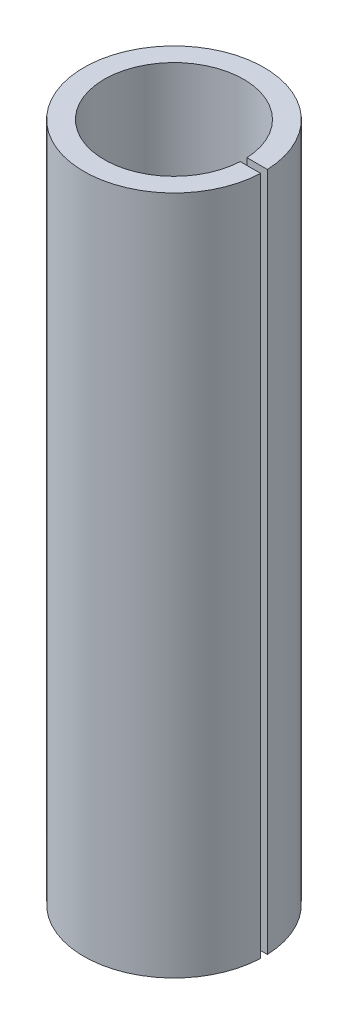
SolidWorks part; units mm, degrees
ref_plane "Front Plane" through (0, 0, 0) normal (0, 0, 1) x (1, 0, 0)
ref_plane "Top Plane" through (0, 0, 0) normal (0, 1, 0) x (1, 0, 0)
ref_plane "Right Plane" through (0, 0, 0) normal (1, 0, 0) x (0, 0, -1)
ref_plane "Plane1" through (0, 0, 0) normal (0, 0, 1) x (1, 0, 0)
sketch "Sketch1" plane through (0, 0, 0) normal (0, 0, 1) x (1, 0, 0)
  line L0 (2.05, 20) -> (2.05, 0)
  line L1 (2.05, 0) -> (2.65, 0)
  line L2 (2.65, 0) -> (2.65, 20)
  line L3 (2.65, 20) -> (2.05, 20)
  line L4 (0, 0) -> (0, 20) construction
revolve "Revolve1" add sketch "Sketch1" angle 360 about L4
ref_plane "Plane2" through (0, 0, 0) normal (1, 0, 0) x (0, 0, -1)
sketch "Sketch2" plane through (0, 0, 0) normal (1, 0, 0) x (0, 0, -1)
  line L0 (-0.1, 0) -> (0.1, 0)
  line L1 (0.1, 0) -> (0.1, 20)
  line L2 (0.1, 20) -> (-0.1, 20)
  line L3 (-0.1, 20) -> (-0.1, 0)
extrude "Cut-Extrude1" cut sketch "Sketch2" along normal blind 5.3
